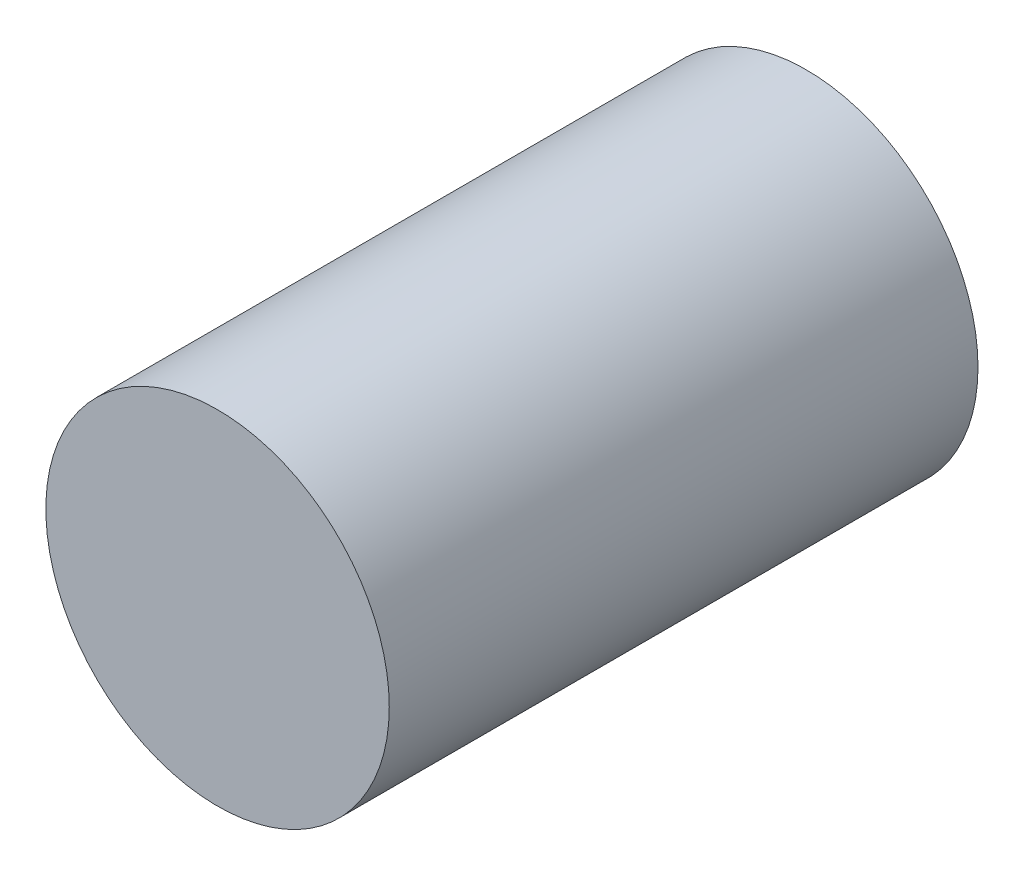
SolidWorks part; units mm, degrees
ref_plane "Front Plane" through (0, 0, 0) normal (0, 0, 1) x (1, 0, 0)
ref_plane "Top Plane" through (0, 0, 0) normal (0, 1, 0) x (1, 0, 0)
ref_plane "Right Plane" through (0, 0, 0) normal (1, 0, 0) x (0, 0, -1)
sketch "Sketch1" plane through (0, 0, 0) normal (0, 0, 1) x (1, 0, 0)
  circle A0 centre (0, 0) radius 7
extrude "Boss-Extrude1" add sketch "Sketch1" along normal blind 24
